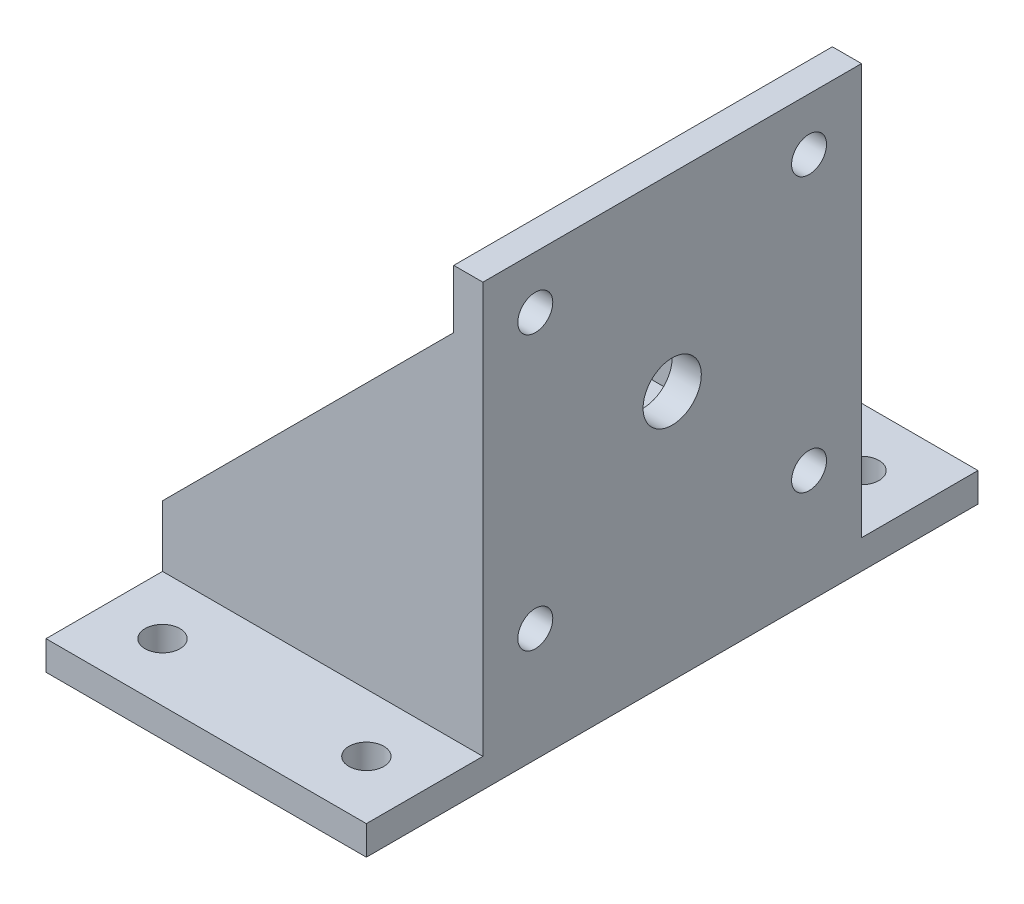
SolidWorks part; units mm, degrees
ref_plane "Front Plane" through (0, 0, 0) normal (0, 0, 1) x (1, 0, 0)
ref_plane "Top Plane" through (0, 0, 0) normal (0, 1, 0) x (1, 0, 0)
ref_plane "Right Plane" through (0, 0, 0) normal (1, 0, 0) x (0, 0, -1)
sketch "Sketch1" plane through (0, 0, 0) normal (0, 0, 1) x (1, 0, 0)
  line L0 (0, 0) -> (0, 60)
  line L1 (0, 60) -> (5, 60)
  line L2 (5, 60) -> (5, -15.5)
  line L3 (5, -15.5) -> (-50, -15.5)
  line L4 (-50, -15.5) -> (-50, 0)
  line L5 (-50, 0) -> (0, 0)
  dimension "D1" = 5
  dimension "D2" = 60
  dimension "D3" = 15.5
  dimension "D4" = 50
extrude "Boss-Extrude1" add sketch "Sketch1" along normal blind 65
sketch "Sketch2" plane through (0, 0, 0) normal (0, 0, -1) x (-1, 0, 0)
  line L0 (50, 0) -> (0, 50)
  line L6 (50, 0) -> (0, 0)
  line L7 (0, 0) -> (0, 60)
  line L8 (0, 60) -> (-5, 60)
  line L9 (-5, 60) -> (-5, -15.5)
  line L10 (-5, -15.5) -> (50, -15.5)
  line L11 (50, -15.5) -> (50, 0)
  line L12 (50, 0) -> (0, 0)
  line L13 (0, 0) -> (0, 60)
  line L14 (0, 60) -> (-5, 60)
  line L15 (-5, 60) -> (-5, -15.5)
  line L16 (-5, -15.5) -> (50, -15.5)
  line L17 (50, -15.5) -> (50, 0)
  dimension "D2" = 45
  dimension "D1" = 0
extrude "Boss-Extrude2" add sketch "Sketch2" against normal blind 5
sketch "Sketch3" plane through (0, 0, 65) normal (0, 0, 1) x (1, 0, 0)
  line L3 (0, 50) -> (-50, 0)
  line L4 (-50, 0) -> (0, 0)
  line L5 (0, 0) -> (0, 50)
  line L7 (-50, 0) -> (0, 0)
  line L8 (0, 0) -> (0, 50)
  line L9 (0, 50) -> (-50, 0)
  dimension "D1" = 0
extrude "Boss-Extrude3" add sketch "Sketch3" against normal blind 5
sketch "Sketch4" plane through (0, 0, 0) normal (-1, 0, 0) x (0, 0, 1)
  line L0 (32.5, 60) -> (32.5, 0)
  line L2 (9, 4) -> (56, 4)
  line L3 (9, 4) -> (9, 51)
  line L4 (5, 0) -> (60, 0)
  line L5 (60, 0) -> (60, 50)
  line L6 (65, 60) -> (0, 60)
  line L7 (60, 50) -> (65, 50)
  line L8 (5, 0) -> (60, 0)
  line L9 (60, 0) -> (60, 50)
  line L10 (65, 60) -> (0, 60)
  line L12 (9, 51) -> (56, 51)
  line L13 (56, 4) -> (56, 51)
  line L14 (9, 4) -> (56, 51) construction
  line L15 (60, 50) -> (65, 50)
  line L16 (65, 50) -> (65, 60)
  line L17 (65, 50) -> (65, 60)
  line L18 (0, 60) -> (0, 50)
  line L19 (0, 60) -> (0, 50)
  line L20 (9, 51) -> (56, 4) construction
  line L22 (5, 50) -> (5, 0)
  line L23 (5, 50) -> (5, 0)
  line L24 (0, 50) -> (5, 50)
  line L25 (0, 50) -> (5, 50)
  circle A0 centre (32.5, 27.5) radius 5
  circle A1 centre (9, 51) radius 3
  circle A2 centre (56, 51) radius 3
  circle A3 centre (56, 4) radius 3
  circle A4 centre (9, 4) radius 3
  point P15 (0, 0)
  point P16 (0, 0)
  dimension "D2" = 10
  dimension "D4" = 6
  dimension "D3" = 47
  dimension "D5" = 27.5
  dimension "D1" = 0
extrude "Cut-Extrude1" cut sketch "Sketch4" against normal through all contours A0 | A1 | A2 | A3 | A4
sketch "Sketch5" plane through (0, -15.5, 0) normal (0, -1, 0) x (1, 0, 0)
  line L0 (-50, -20) -> (5, -20)
  line L1 (5, 85) -> (-50, 85)
  line L4 (-50, 0) -> (5, 0)
  line L5 (5, 0) -> (5, 65)
  line L6 (5, 65) -> (-50, 65)
  line L7 (-50, 65) -> (-50, 0)
  line L8 (-50, 0) -> (5, 0)
  line L9 (5, -20) -> (5, 85)
  line L10 (5, 65) -> (-50, 65)
  line L11 (-50, 85) -> (-50, -20)
  line M5 (-50, 0) -> (5, 0)
  line M7 (5, 65) -> (-50, 65)
  dimension "D1" = 0
  dimension "D2" = 20
  dimension "D3" = 20
extrude "Boss-Extrude4" add sketch "Sketch5" against normal blind 5 contours L11 L0 L9 M5 | L1 L11 L9 M7
sketch "Sketch6" plane through (0, -10.5, 0) normal (0, 1, 0) x (1, 0, 0)
  line L0 (5, 10) -> (-50, 10) construction
  line L4 (-50, 0) -> (5, 0)
  line L5 (5, 0) -> (5, 20)
  line L6 (5, 20) -> (-50, 20)
  line L7 (-50, 20) -> (-50, 0)
  line L8 (-50, 0) -> (5, 0)
  line L9 (5, 0) -> (5, 20)
  line L10 (5, 20) -> (-50, 20)
  line L11 (-50, 20) -> (-50, 0)
  line L13 (0, -32.5) -> (-50, -32.5) construction
  line L17 (-50, -60) -> (0, -60)
  line L18 (0, -60) -> (0, -5)
  line L19 (0, -5) -> (-50, -5)
  line L20 (-50, -5) -> (-50, -60)
  line L21 (-50, -60) -> (0, -60)
  line L22 (0, -60) -> (0, -5)
  line L23 (0, -5) -> (-50, -5)
  line L24 (-50, -5) -> (-50, -60)
  circle A0 centre (-5, 10) radius 3
  circle A1 centre (-40, 10) radius 3
  circle A2 centre (-5, -75) radius 3
  circle A3 centre (-40, -75) radius 3
  dimension "D2" = 6
  dimension "D3" = 10
  dimension "D4" = 10
  dimension "D1" = 0
  dimension "D5" = 0
extrude "Cut-Extrude2" cut sketch "Sketch6" against normal blind 5 contours A1 | A0 | A2 | A3
